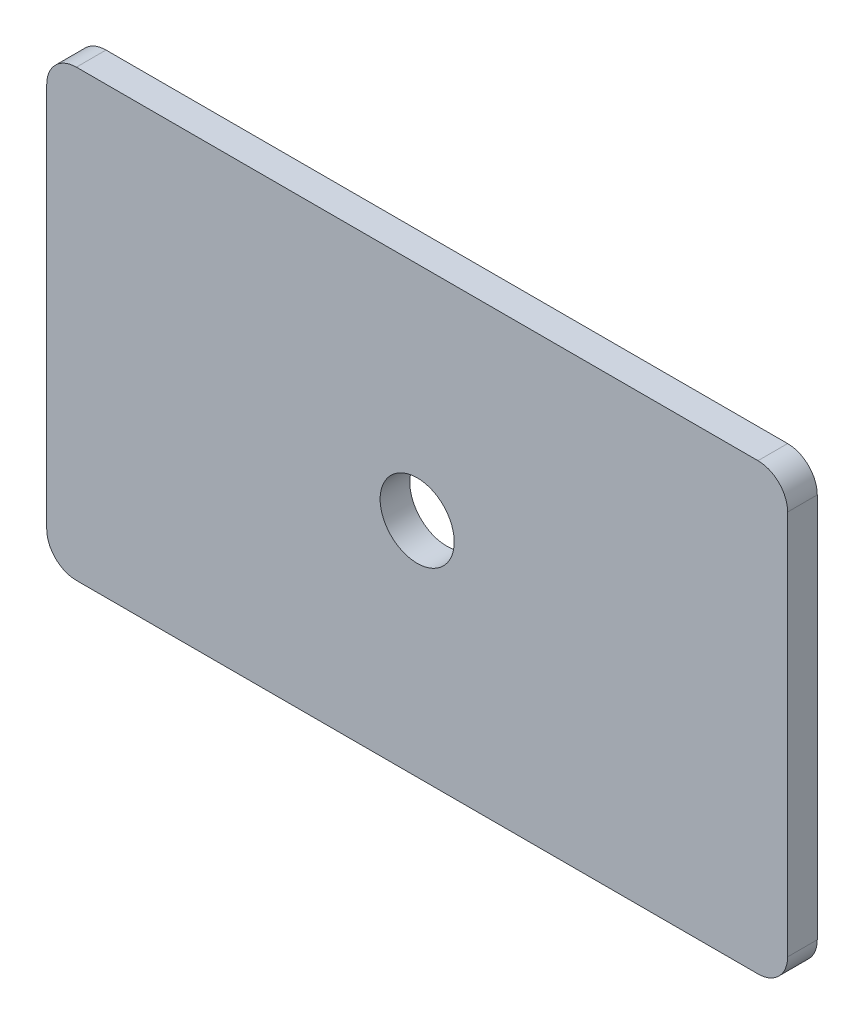
SolidWorks part; units mm, degrees
ref_plane "Vorne" through (0, 0, 0) normal (0, 0, 1) x (1, 0, 0)
ref_plane "Oben" through (0, 0, 0) normal (0, 1, 0) x (1, 0, 0)
ref_plane "Rechts" through (0, 0, 0) normal (1, 0, 0) x (0, 0, -1)
ref_plane "E_Boden" through (0, 1, 0) normal (0, 1, 0) x (1, 0, 0)
sketch "Skizze1" plane through (0, 0, 0) normal (0, 0, 1) x (1, 0, 0)
  line L0 (-20.2005, 0) -> (23.2167, 0) construction
  line L1 (0, -7.2428) -> (0, 9.7431) construction
  line L3 (-125, 75) -> (125, 75)
  line L4 (-125, 75) -> (-125, -75)
  line L5 (-125, -75) -> (125, -75)
  line L6 (125, 75) -> (125, -75)
  circle A0 centre (0, 0) radius 12.5
  point P11 (0, 0)
  dimension "D3" = 25
  dimension "D1" = 250
  dimension "D2" = 150
extrude "Aufsatz-Linear austragen1" add sketch "Skizze1" along normal blind 10
fillet "Verrundung1" radius 10 4 edges at (-125, -75, 5) (125, -75, 5) (125, 75, 5) (-125, 75, 5)
